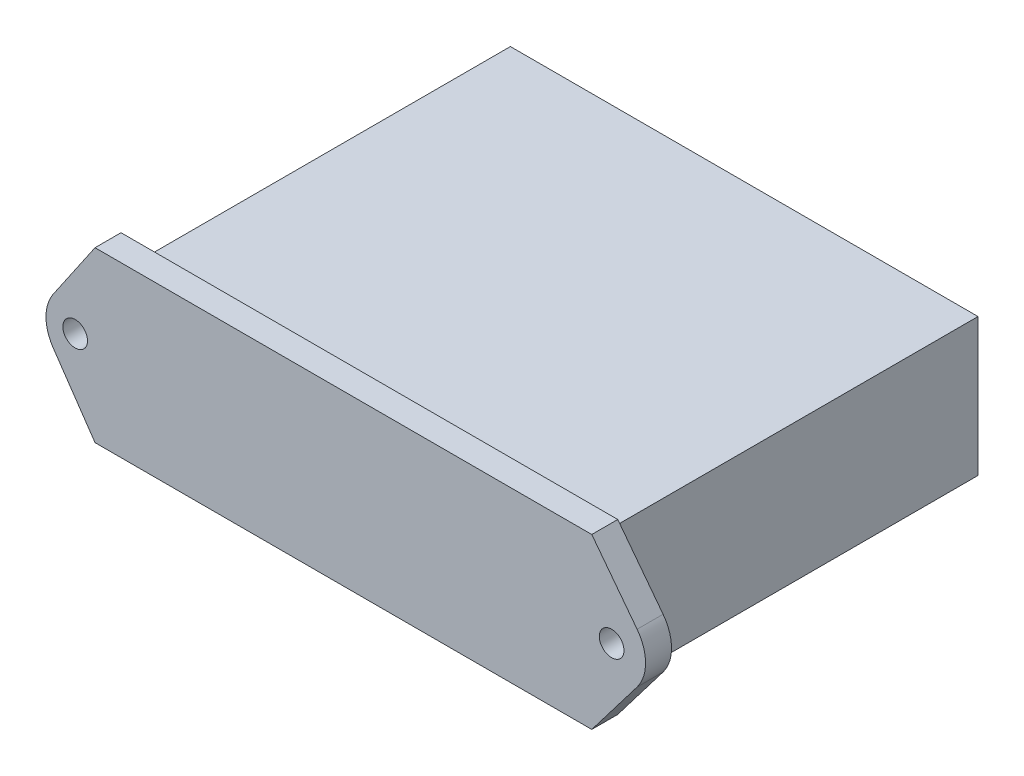
SolidWorks part; units mm, degrees
ref_plane "Front Plane" through (0, 0, 0) normal (0, 0, 1) x (1, 0, 0)
ref_plane "Top Plane" through (0, 0, 0) normal (0, 1, 0) x (1, 0, 0)
ref_plane "Right Plane" through (0, 0, 0) normal (1, 0, 0) x (0, 0, -1)
sketch "Sketch1" plane through (0, 0, 0) normal (0, 1, 0) x (1, 0, 0)
  line L1 (0, 0) -> (72, 0)
  line L2 (0, 0) -> (0, 57.2)
  line L3 (0, 57.2) -> (72, 57.2)
  line L4 (72, 0) -> (72, 57.2)
  dimension "D1" = 72
  dimension "D2" = 57.2
extrude "Boss-Extrude1" add sketch "Sketch1" along normal blind 21.2
sketch "Sketch2" plane through (0, 0, 0) normal (0, 0, 1) x (1, 0, 0)
  line L0 (-2.7539, 23.6) -> (73.7307, 23.6)
  line L1 (-2.7539, -2.4) -> (73.7307, -2.4)
  line L2 (83.65, 10.6) -> (-11.65, 10.6) construction
  line L4 (36, 21.2) -> (36, 0) construction
  line L5 (0, 21.2) -> (72, 21.2) construction
  line L6 (0, 0) -> (72, 0) construction
  line L7 (-2.7539, 23.6) -> (-11.65, 10.6)
  line L8 (-11.65, 10.6) -> (-2.7539, -2.4)
  line L9 (73.7307, 23.6) -> (83.65, 10.6)
  line L10 (83.65, 10.6) -> (73.7307, -2.4)
  dimension "D1" = 95.3
  dimension "D2" = 47.65
  dimension "D3" = 26
  dimension "D4" = 13
extrude "Boss-Extrude2" add sketch "Sketch2" along normal blind 4
fillet "Fillet1" radius 6.35 2 edges at (-11.65, 10.6, 2) (83.65, 10.6, 2)
sketch "Sketch3" plane through (0, 0, 4) normal (0, 0, 1) x (1, 0, 0)
  line L0 (-16.1783, 10.6) -> (87.6061, 10.6) construction
  line L1 (35.4884, 23.6) -> (35.4884, -2.4) construction
  line L2 (73.7307, 23.6) -> (-2.7539, 23.6) construction
  line L3 (-2.7539, -2.4) -> (73.7307, -2.4) construction
  circle A0 centre (-5.8116, 10.6) radius 1.9
  circle A1 centre (76.7884, 10.6) radius 1.9
  dimension "D1" = 3.8
  dimension "D3" = 41.3
  dimension "D2" = 82.6
extrude "Cut-Extrude1" cut sketch "Sketch3" against normal through all
